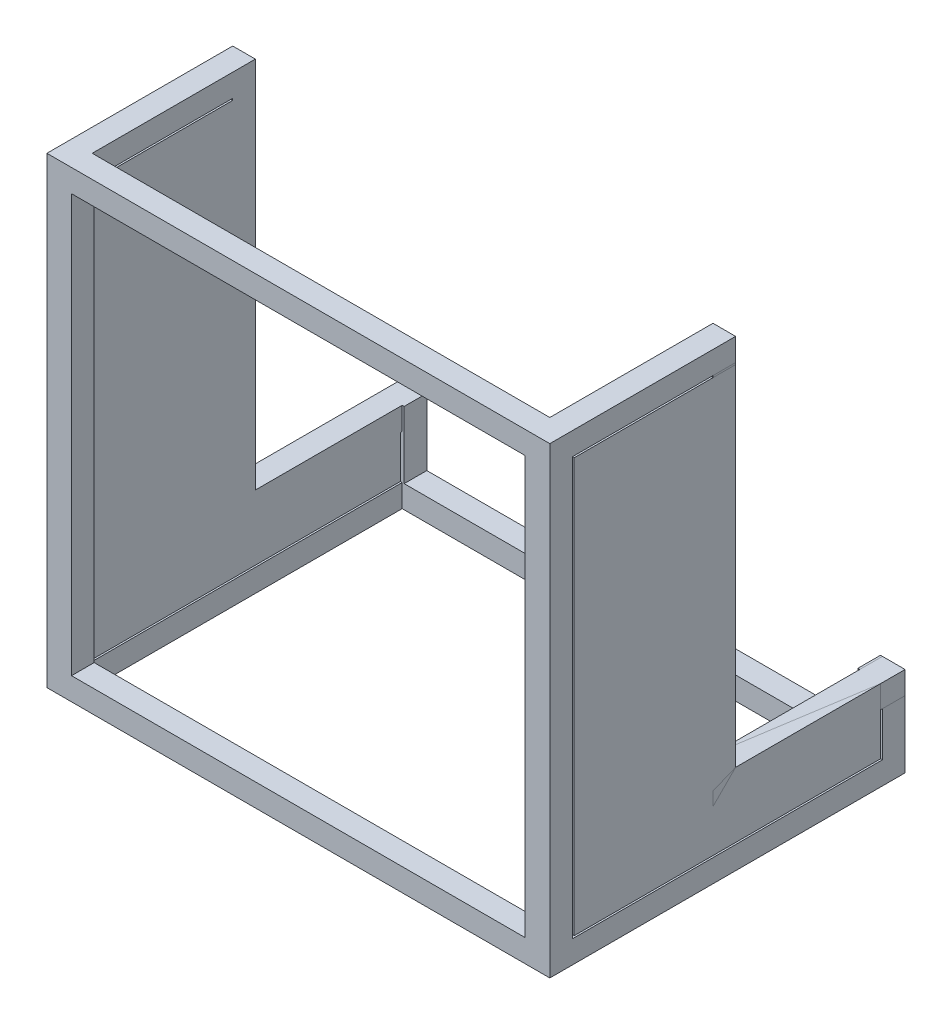
SolidWorks part; units mm, degrees
ref_plane "Alzado" through (0, 0, 0) normal (0, 0, 1) x (1, 0, 0)
ref_plane "Planta" through (0, 0, 0) normal (0, 1, 0) x (1, 0, 0)
ref_plane "Vista lateral" through (0, 0, 0) normal (1, 0, 0) x (0, 0, -1)
sketch "Croquis1" plane through (0, 0, 0) normal (0, 0, 1) x (1, 0, 0)
  line L1 (-281.9, 259.4) -> (281.9, 259.4)
  line L2 (-281.9, 259.4) -> (-281.9, -259.4)
  line L3 (-281.9, -259.4) -> (281.9, -259.4)
  line L4 (281.9, 259.4) -> (281.9, -259.4)
  line L5 (-281.9, 259.4) -> (281.9, -259.4) construction
  line L6 (-281.9, -259.4) -> (281.9, 259.4) construction
  line L7 (-254.2968, 234) -> (254.2968, 234)
  line L8 (-254.2968, 234) -> (-254.2968, -234)
  line L9 (-254.2968, -234) -> (254.2968, -234)
  line L10 (254.2968, 234) -> (254.2968, -234)
  line L11 (-254.2968, 234) -> (254.2968, -234) construction
  line L12 (-254.2968, -234) -> (254.2968, 234) construction
  point P0 (0, 0)
  point P6 (0, 0)
  dimension "D1" = 563.8
  dimension "D2" = 518.8
  dimension "D3" = 25.4
extrude "Saliente-Extruir1" add sketch "Croquis1" against normal blind 398.31
sketch "Croquis2" plane through (281.9, 0, 0) normal (1, 0, 0) x (0, 0, -1)
  line L0 (0, 0) -> (398.31, 0) construction
  line L1 (398.31, -259.4) -> (398.31, 259.4) construction
  line L2 (398.31, 0) -> (199.155, 0) construction
  line L3 (199.155, 0) -> (199.155, 259.4) construction
  line L4 (398.31, 259.4) -> (0, 259.4) construction
  line L5 (0, -259.4) -> (0, 259.4) construction
  line L6 (25.4, 234) -> (372.91, 234)
  line L7 (25.4, 234) -> (25.4, -234)
  line L8 (25.4, -234) -> (372.91, -234)
  line L9 (372.91, 234) -> (372.91, -234)
  line L10 (25.4, 234) -> (372.91, -234) construction
  line L11 (25.4, -234) -> (372.91, 234) construction
  dimension "D1" = 25.4
  dimension "D2" = 25.4
extrude "Cortar-Extruir1" cut sketch "Croquis2" against normal up to surface (563.8 mm away) up to face at (-281.9, 0, -199.155)
sketch "Croquis3" plane through (0, 259.4, 0) normal (0, 1, 0) x (1, 0, 0)
  line L0 (0, 0) -> (0, 398.31) construction
  line L1 (281.9, 398.31) -> (-281.9, 398.31) construction
  line L2 (0, 398.31) -> (0, 199.155) construction
  line L3 (0, 199.155) -> (-281.9, 199.155) construction
  line L4 (-281.9, 398.31) -> (-281.9, 0) construction
  line L5 (281.9, 398.31) -> (281.9, 0) construction
  line L6 (256.5, 372.91) -> (-256.5, 372.91)
  line L7 (256.5, 372.91) -> (256.5, 25.4)
  line L8 (256.5, 25.4) -> (-256.5, 25.4)
  line L9 (-256.5, 372.91) -> (-256.5, 25.4)
  line L10 (256.5, 372.91) -> (-256.5, 25.4) construction
  line L11 (256.5, 25.4) -> (-256.5, 372.91) construction
  line L12 (281.9, 0) -> (-281.9, 0) construction
  dimension "D1" = 25.4
  dimension "D2" = 25.4
extrude "Cortar-Extruir2" cut sketch "Croquis3" against normal blind 410
sketch "Croquis4" plane through (0, -259.4, 0) normal (0, -1, 0) x (1, 0, 0)
  line L0 (0, 0) -> (0, -398.31) construction
  line L1 (-281.9, -398.31) -> (281.9, -398.31) construction
  line L2 (0, -398.31) -> (0, -199.155) construction
  line L3 (0, -199.155) -> (255.26, -199.155) construction
  line L4 (-281.9, 0) -> (281.9, 0) construction
  line L5 (256.5, -25.4) -> (-256.5, -25.4)
  line L6 (256.5, -25.4) -> (256.5, -372.91)
  line L7 (256.5, -372.91) -> (-256.5, -372.91)
  line L8 (-256.5, -25.4) -> (-256.5, -372.91)
  line L9 (256.5, -25.4) -> (-256.5, -372.91) construction
  line L10 (256.5, -372.91) -> (-256.5, -25.4) construction
  line L11 (281.9, -398.31) -> (281.9, 0) construction
  dimension "D1" = 25.4
  dimension "D2" = 25.4
extrude "Cortar-Extruir3" cut sketch "Croquis4" against normal blind 40
sketch "Croquis5" plane through (281.9, 0, 0) normal (1, 0, 0) x (0, 0, -1)
  line L0 (372.91, -234) -> (372.91, 234) construction
  line L1 (27.4, 232) -> (370.91, 232)
  line L2 (27.4, 232) -> (27.4, -232)
  line L3 (27.4, -232) -> (370.91, -232)
  line L4 (370.91, 232) -> (370.91, -232)
  line L5 (27.4, 232) -> (370.91, -232) construction
  line L6 (27.4, -232) -> (370.91, 232) construction
  line L7 (372.91, 234) -> (25.4, 234) construction
  line L8 (25.4, -234) -> (372.91, -234) construction
  line L9 (25.4, 234) -> (25.4, -234) construction
  point P0 (199.155, 0)
  dimension "D1" = 2
  dimension "D2" = 2
  dimension "D3" = 2
  dimension "D4" = 2
extrude "Saliente-Extruir2" add sketch "Croquis5" against normal blind 25.4 separate body
sketch "Croquis6" plane through (-281.9, 0, 0) normal (-1, 0, 0) x (0, 0, 1)
  line L0 (-370.91, 232) -> (-27.4, 232)
  line L1 (-27.4, 232) -> (-27.4, -232)
  line L2 (-27.4, -232) -> (-370.91, -232)
  line L3 (-370.91, -232) -> (-370.91, 232)
extrude "Saliente-Extruir3" add sketch "Croquis6" against normal blind 25.4 separate body
sketch "Croquis7" plane through (-281.9, 0, 0) normal (-1, 0, 0) x (0, 0, 1)
  line L0 (-398.31, 259.4) -> (-208.31, 259.4)
  line L1 (-398.31, 259.4) -> (0, 259.4) construction
  line L2 (-208.31, 259.4) -> (-208.31, -159)
  line L3 (-208.31, -159) -> (0, -159) construction
  line L4 (0, 259.4) -> (0, -259.4) construction
  line L5 (-208.31, 259.4) -> (0, 259.4) construction
  line L6 (0, 259.4) -> (0, -159) construction
  line L7 (-208.31, 234) -> (-25.4, 234) construction
  line L8 (-372.91, 234) -> (-25.4, 234) construction
  line L9 (-25.4, 234) -> (-25.4, -159) construction
  line L10 (-25.4, -234) -> (-372.91, -234) construction
  line L11 (-208.31, -159) -> (-398.31, -159)
  line L12 (-398.31, 259.4) -> (-398.31, -259.4) construction
  line L13 (-398.31, -159) -> (-398.31, 259.4)
  dimension "D2" = 75
sketch "Croquis8" plane through (-281.9, 0, 0) normal (-1, 0, 0) x (0, 0, 1)
  line L0 (-208.31, 232) -> (-208.31, -159)
  line L1 (-27.4, 232) -> (-370.91, 232) construction
  line L2 (-27.4, -159) -> (-208.31, -159)
  line L3 (-27.4, -232) -> (-27.4, 232) construction
  line L4 (-208.31, 232) -> (-27.4, 232)
  line L5 (-27.4, 232) -> (-27.4, -159)
extrude "Cortar-Extruir6" cut sketch "Croquis7" against normal blind 584
sketch "Croquis9" plane through (281.9, 0, 0) normal (1, 0, 0) x (0, 0, -1)
  line L0 (208.31, 234) -> (208.31, -159)
  line L1 (208.31, 232) -> (208.31, -159) construction
  line L2 (208.31, -159) -> (398.31, -159)
  line L3 (398.31, -159) -> (398.31, -184.4)
  line L5 (182.91, 234) -> (182.91, -184.4)
  line L6 (182.91, -184.4) -> (398.31, -184.4)
  line L7 (208.31, 234) -> (182.91, 234)
  dimension "D1" = 25.4
extrude "Saliente-Extruir4" add sketch "Croquis9" against normal blind 25.4 separate body
sketch "Croquis10" plane through (-281.9, 0, 0) normal (-1, 0, 0) x (0, 0, 1)
  line L0 (-182.91, 234) -> (-208.31, 234)
  line L1 (-208.31, 234) -> (-208.31, -159)
  line L2 (-208.31, -159) -> (-372.91, -159)
  line L3 (-372.91, -159) -> (-372.91, -184.4)
  line L4 (-182.91, -184.4) -> (-398.31, -184.4) construction
  line L5 (-372.91, -234) -> (-372.91, -159) construction
  line L6 (-372.91, -184.4) -> (-182.91, -184.4)
  line L7 (-182.91, -184.4) -> (-182.91, 234)
extrude "Saliente-Extruir5" add sketch "Croquis10" against normal blind 25.4 and the other way blind 0.02
